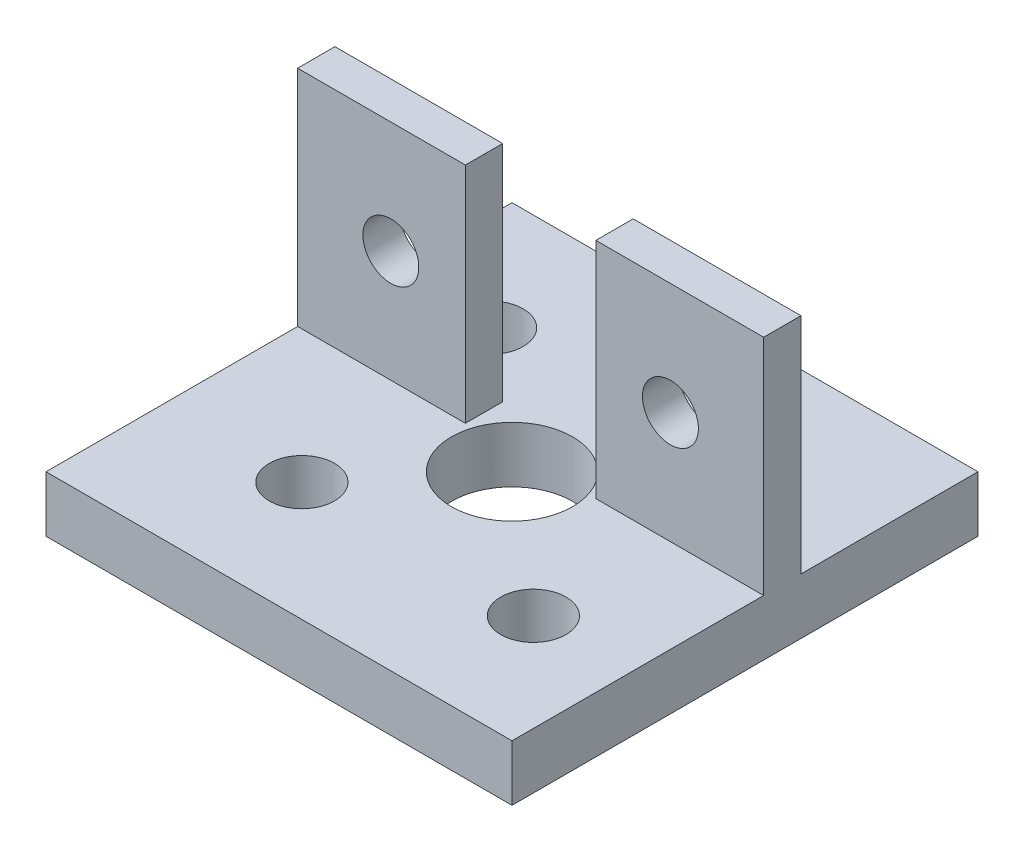
SolidWorks part; units mm, degrees
material "PLA"
ref_plane "Front Plane" through (0, 0, 0) normal (0, 0, 1) x (1, 0, 0)
ref_plane "Top Plane" through (0, 0, 0) normal (0, 1, 0) x (1, 0, 0)
ref_plane "Right Plane" through (0, 0, 0) normal (1, 0, 0) x (0, 0, -1)
sketch "Sketch1" plane through (0, 0, 0) normal (0, 1, 0) x (1, 0, 0)
  line L5 (-11.3868, -13.5218) -> (11.3868, 13.5218) construction
  line L6 (-13.5218, 11.3868) -> (13.5218, -11.3868) construction
  circle A0 centre (-7.2667, 6.1193) radius 1.75
  circle A1 centre (5.1531, 6.1193) radius 1.75
  circle A2 centre (-5.1531, -6.1193) radius 1.75
  circle A3 centre (7.2667, -6.1193) radius 1.75
  point P0 (0, 0)
  dimension "D2" = 3.5
  dimension "D3" = 3.5
  dimension "D4" = 9.5
  dimension "D5" = 8
sketch "Sketch4" plane through (0, 0, 0) normal (0, 1, 0) x (1, 0, 0)
  line L1 (-12.5, 12.5) -> (12.5, 12.5)
  line L2 (-12.5, 12.5) -> (-12.5, -12.5)
  line L3 (-12.5, -12.5) -> (12.5, -12.5)
  line L4 (12.5, 12.5) -> (12.5, -12.5)
  line L5 (-12.5, 12.5) -> (12.5, -12.5) construction
  line L6 (-12.5, -12.5) -> (12.5, 12.5) construction
  line L7 (0, -55) -> (0, 55) construction
  point P0 (0, 0)
  dimension "D1" = 25
  dimension "D2" = 25
extrude "Boss-Extrude2" add sketch "Sketch4" along normal blind 3
extrude "Cut-Extrude3" cut sketch "Sketch1" along normal through all
sketch "Sketch5" plane through (0, 3, 0) normal (0, 1, 0) x (1, 0, 0)
  line L0 (-12.5, 0) -> (12.5, 0) construction
  line L1 (-12.5, 12.5) -> (-12.5, -12.5) construction
  line L2 (12.5, -12.5) -> (12.5, 12.5) construction
  line L7 (3.5, 3) -> (12.5, 3)
  line L8 (-12.5, 3) -> (-3.5, 3)
  line L9 (-12.5, 3) -> (-12.5, 1)
  line L10 (-12.5, 1) -> (-3.5, 1)
  line L11 (12.5, 3) -> (12.5, 1)
  line L13 (-3.5, 3) -> (-3.5, 1)
  line L15 (3.5, 3) -> (3.5, 1)
  line L16 (-3.5, 3) -> (3.5, 3) construction
  line L23 (3.5, 1) -> (12.5, 1)
  point P10 (0, 0)
  point P11 (0, 3)
  line M9 (12.5, -12.5) -> (12.5, 12.5)
  line M11 (-12.5, 12.5) -> (-12.5, -12.5)
  dimension "D1" = 2
  dimension "D2" = 1
  dimension "D3" = 9
extrude "Boss-Extrude3" add sketch "Sketch5" along normal blind 12 contours L13 L8 L10 M11 | L15 L23 L7 M9
sketch "Sketch6" plane through (0, 0, 0) normal (0, -1, 0) x (1, 0, 0)
  circle A1 centre (0, 0) radius 3.25
  dimension "D1" = 6.5
extrude "Cut-Extrude4" cut sketch "Sketch6" against normal through all
sketch "Sketch7" plane through (0, 0, -3) normal (0, 0, -1) x (-1, 0, 0)
  line L0 (-12.5, 15) -> (-12.5, 3) construction
  line L1 (0, 1.65) -> (0, -1.65) construction
  circle A0 centre (-7.5, 9) radius 1.5
  circle A1 centre (7.5, 9) radius 1.5
  point P5 (-12.5, 9)
  dimension "D2" = 3
  dimension "D1" = 5
extrude "Cut-Extrude5" cut sketch "Sketch7" against normal up to surface (2 mm away) contours A0 | A1 up to face at (8, 9, -1)
